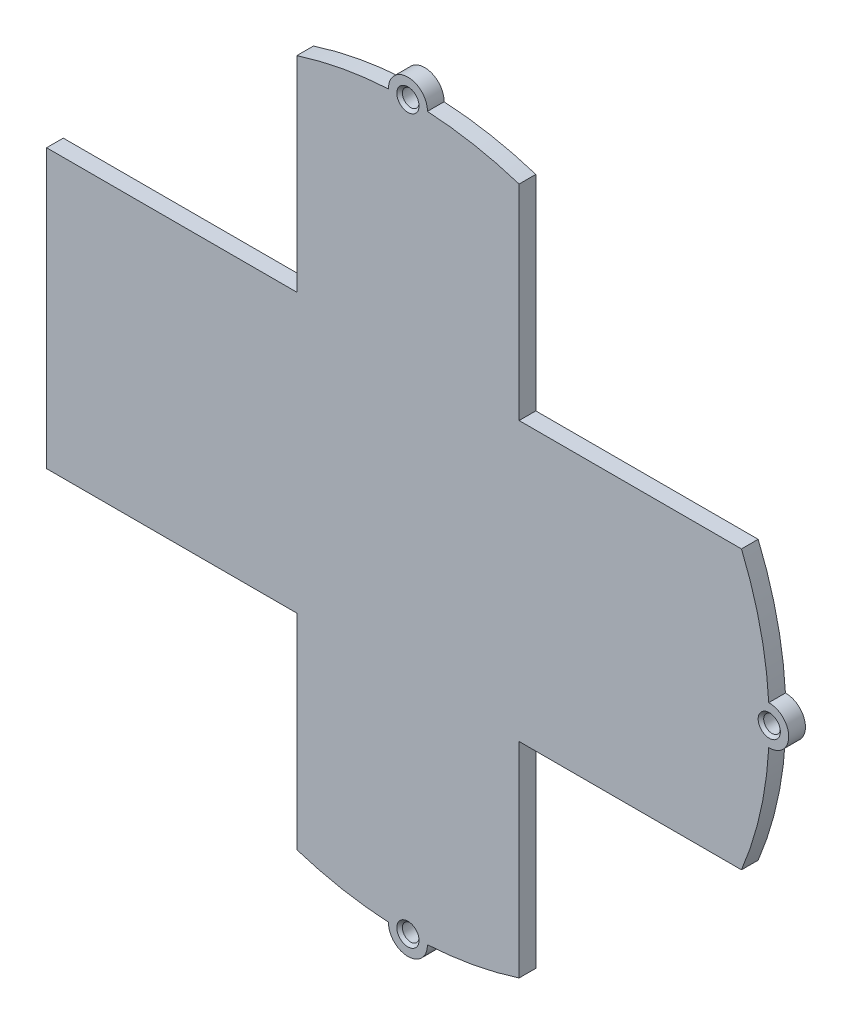
SolidWorks part; units mm, degrees
ref_plane "前视基准面" through (0, 0, 0) normal (0, 0, 1) x (1, 0, 0)
ref_plane "上视基准面" through (0, 0, 0) normal (0, 1, 0) x (1, 0, 0)
ref_plane "右视基准面" through (0, 0, 0) normal (1, 0, 0) x (0, 0, -1)
sketch "草图1" plane through (0, 0, 0) normal (0, 0, 1) x (1, 0, 0)
  line L0 (20, -25) -> (20, -61.8466)
  line L1 (-60, 25) -> (-20, 25)
  line L3 (-60, -25) -> (-20, -25)
  line L6 (-20, 61.8466) -> (-20, 25)
  line L8 (20, 61.8466) -> (20, 25)
  line L9 (-20, -25) -> (-20, -61.8466)
  line L10 (20, 25) -> (60, 25)
  line L11 (20, -25) -> (60, -25)
  arc A1 (-60, 25) -> (-60, -25) centre (0, 0) ccw
  arc A2 (20, 61.8466) -> (-20, 61.8466) centre (0, 0) ccw
  arc A3 (60, -25) -> (60, 25) centre (0, 0) ccw
  arc A4 (-20, -61.8466) -> (20, -61.8466) centre (0, 0) ccw
  dimension "D1" = 130
  dimension "D2" = 40
  dimension "D3" = 50
  dimension "D4" = 25
  dimension "D5" = 20
extrude "凸台-拉伸1" add sketch "草图1" along normal blind 3
sketch "草图2" plane through (0, 0, 3) normal (0, 0, 1) x (1, 0, 0)
  circle A0 centre (65, 0) radius 3.5
  arc A1 (60, -25) -> (60, 25) centre (0, 0) ccw construction
  circle A2 centre (0, 65) radius 3.5
  arc A3 (20, 61.8466) -> (-20, 61.8466) centre (0, 0) ccw construction
  circle A4 centre (0, -65) radius 3.5
  arc A5 (-20, -61.8466) -> (20, -61.8466) centre (0, 0) ccw construction
  dimension "D1" = 7
  dimension "D2" = 7
  dimension "D3" = 7
extrude "凸台-拉伸2" add sketch "草图2" against normal blind 3
sketch "草图3" plane through (0, 0, 3) normal (0, 0, 1) x (1, 0, 0)
  circle A0 centre (0, 65) radius 1.5
  circle A1 centre (65, 0) radius 1.5
  circle A2 centre (0, -65) radius 1.5
  dimension "D1" = 3
  dimension "D2" = 3
  dimension "D3" = 3
extrude "切除-拉伸1" cut sketch "草图3" against normal blind 3
chamfer "倒角1" distance 0.5 angle 45 3 edges at (1.5, 65, 3) (66.5, 0, 3) (1.5, -65, 3)
sketch "草图4" plane through (0, 0, 3) normal (0, 0, 1) x (1, 0, 0)
  line L0 (-60, 25) -> (-65, 25)
  line L1 (-65, 25) -> (-65, -25)
  line L2 (-65, -25) -> (-60, -25)
  arc A0 (-60, 25) -> (-60, -25) centre (0, 0) ccw construction
  arc A1 (-60, 25) -> (-60, -25) centre (0, 0) ccw
  arc M23 (-60, 25) -> (-60, -25) centre (0, 0) ccw
  dimension "D1" = 65
extrude "凸台-拉伸4" add sketch "草图4" against normal blind 3 contours L1 L2 M23 | L0 L1 M23
